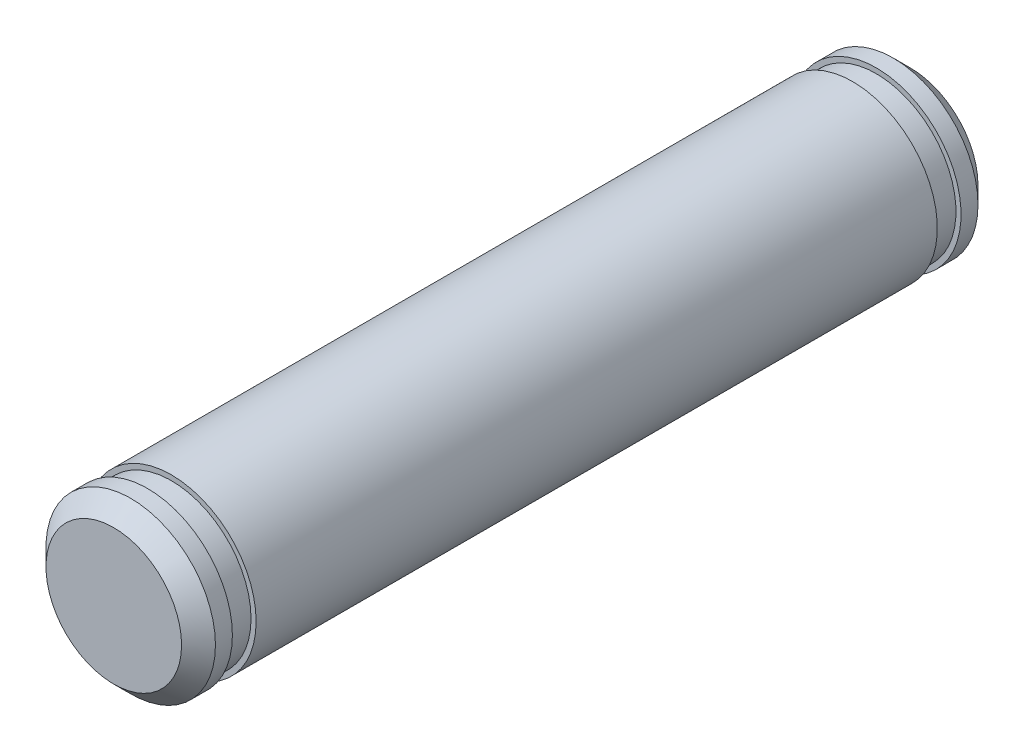
SolidWorks part; units mm, degrees
material "Chromowa stal nierdzewna"
ref_plane "Płaszczyzna przednia" through (0, 0, 0) normal (0, 0, 1) x (1, 0, 0)
ref_plane "Płaszczyzna górna" through (0, 0, 0) normal (0, 1, 0) x (1, 0, 0)
ref_plane "Płaszczyzna prawa" through (0, 0, 0) normal (1, 0, 0) x (0, 0, -1)
sketch "Szkic1" plane through (0, 0, 0) normal (0, 0, 1) x (1, 0, 0)
  circle A0 centre (0, 0) radius 2.5
  dimension "D1" = 5
extrude "Dodanie-wyciągnięcie1" add sketch "Szkic1" along normal blind 23.5
chamfer "Sfazowanie1" distance 0.5 angle 45 2 edges at (2.5, 0, 0) (2.5, 0, 23.5)
sketch "Szkic2" plane through (0, 0, 23.5) normal (0, 0, 1) x (1, 0, 0)
  circle A0 centre (0, 0) radius 2.5
  circle A1 centre (0, 0) radius 2.35
  dimension "D1" = 5
  dimension "D2" = 4.7
extrude "Wytnij-wyciągnięcie1" cut sketch "Szkic2" against normal blind 0.7 from offset 1 offset against normal yes
sketch "Szkic3" plane through (0, 0, 0) normal (0, 0, -1) x (-1, 0, 0)
  circle A0 centre (0, 0) radius 2.35
  circle A1 centre (0, 0) radius 2.5
  dimension "D1" = 5
  dimension "D2" = 4.7
extrude "Wytnij-wyciągnięcie2" cut sketch "Szkic3" against normal blind 0.7 from offset 1 offset against normal yes
